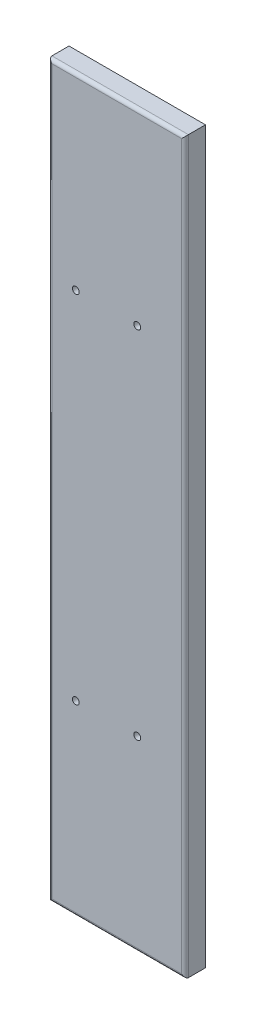
SolidWorks part; units mm, degrees
material "Pine"
ref_plane "Front Plane" through (0, 0, 0) normal (0, 0, 1) x (1, 0, 0)
ref_plane "Top Plane" through (0, 0, 0) normal (0, 1, 0) x (1, 0, 0)
ref_plane "Right Plane" through (0, 0, 0) normal (1, 0, 0) x (0, 0, -1)
sketch "Sketch1" plane through (0, 0, 0) normal (0, 0, 1) x (1, 0, 0)
  line L0 (-50.8, 25.4) -> (-53.975, 25.4)
  line L2 (-53.975, 174.625) -> (73.025, 174.625)
  line L3 (73.025, 174.625) -> (73.025, -504.825)
  line L4 (73.025, -504.825) -> (-53.975, -504.825)
  line L6 (-53.975, -504.825) -> (-53.975, 174.625)
extrude "Boss-Extrude1" add sketch "Sketch1" along normal blind 19.05 contours L3 L4 L6 L2
hole_wizard "1/4 (0.25) Diameter Hole1" positions "Sketch3" profile "Sketch4" hole size "1/4" standard "ANSI Inch" end condition through all
sketch "Sketch3" plane through (0, 0, 19.05) normal (0, 0, 1) x (1, 0, 0)
  point P0 (-28.575, 0)
  point P3 (28.575, 0)
  point P6 (-28.575, -330.9118)
  point P9 (28.575, -330.9118)
sketch "Sketch4" plane through (-28.575, 0, 19.05) normal (1, 0, 0) x (0, -1, 0)
  line L0 (0, 0) -> (0, 19.05)
  line L1 (0, 19.05) -> (3.937, 19.05)
  line L2 (3.175, 18.1734) -> (3.175, 0)
  line L5 (3.175, 0) -> (0, 0)
  line L7 (3.937, 19.05) -> (3.175, 18.1734)
  line L8 (-3.937, 19.05) -> (-3.175, 18.1734) construction
  line L11 (0, -6.35) -> (0, 107.95) construction
  dimension "Thru Hole Dia." = 6.35
  dimension "Thru Hole Depth" = 19.05
  dimension "Far C'Sink Dia." = 7.874
  dimension "Far C'Sink Angle" = 82
fillet "Fillet1" radius 3.175 4 edges at (9.525, 174.625, 19.05) (9.525, -504.825, 19.05) (73.025, -165.1, 19.05) (-53.975, -165.1, 19.05)
